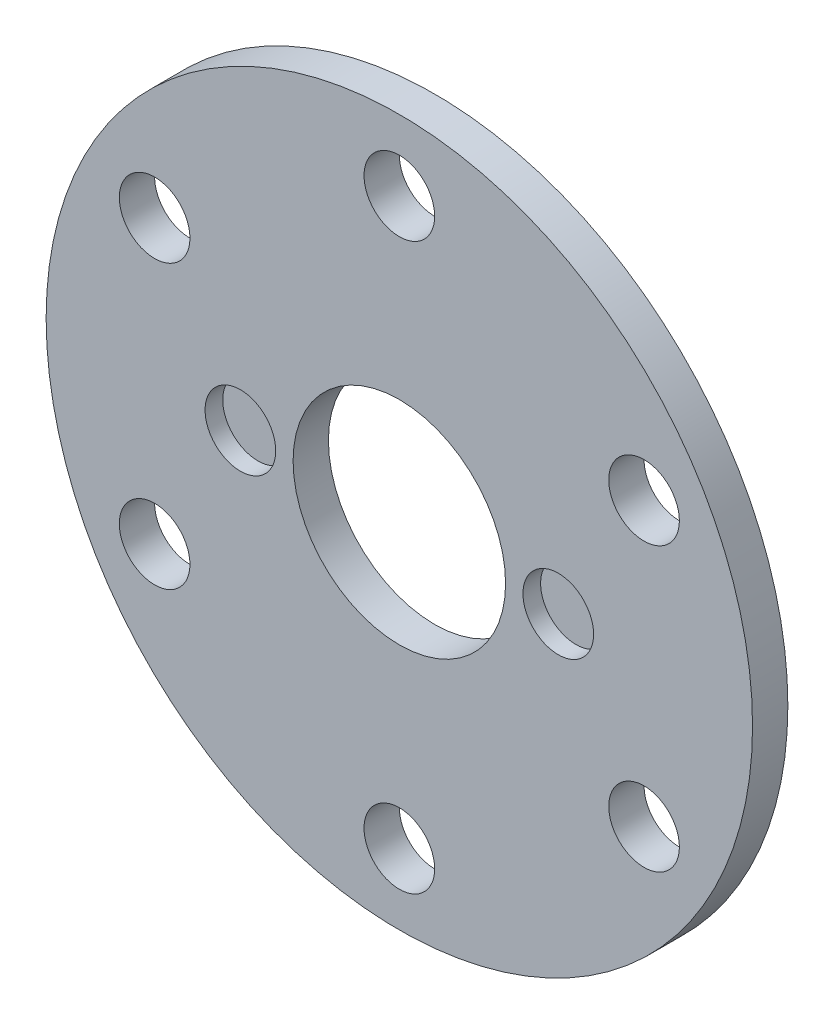
SolidWorks part; units mm, degrees
ref_plane "Front Plane" through (0, 0, 0) normal (0, 0, 1) x (1, 0, 0)
ref_plane "Top Plane" through (0, 0, 0) normal (0, 1, 0) x (1, 0, 0)
ref_plane "Right Plane" through (0, 0, 0) normal (1, 0, 0) x (0, 0, -1)
sketch "Sketch1" plane through (0, 0, 191.2017) normal (0, 0, 1) x (1, 0, 0)
  line L0 (0, 762.7561) -> (0, 788.1561) construction
  line L1 (0, 788.1561) -> (0, 794.5061) construction
  circle A0 centre (0, 762.7561) radius 15.875 construction
  circle A1 centre (0, 762.7561) radius 15.875
  circle A2 centre (0, 762.7561) radius 9.525 construction
  circle A3 centre (0, 762.7561) radius 9.525
  circle A4 centre (-14.2875, 762.7561) radius 3.8735 construction
  circle A5 centre (14.2875, 762.7561) radius 3.8735 construction
  circle A6 centre (-14.2875, 762.7561) radius 3.8735 construction
  circle A7 centre (14.2875, 762.7561) radius 3.8735 construction
  circle A8 centre (0, 762.7561) radius 31.75
  circle A9 centre (0, 788.1561) radius 3.175
  circle A10 centre (21.997, 775.4561) radius 3.175
  circle A11 centre (21.997, 750.0561) radius 3.175
  circle A12 centre (0, 737.3561) radius 3.175
  circle A13 centre (-21.997, 750.0561) radius 3.175
  circle A14 centre (-21.997, 775.4561) radius 3.175
  point P28 (0, 762.7561)
  circle M1 centre (0, 762.7561) radius 15.875
  circle M2 centre (0, 762.7561) radius 9.5504
  dimension "D1" = 63.5
  dimension "D3" = 6.35
  dimension "D2" = 6.35
extrude "Boss-Extrude1" add sketch "Sketch1" along normal blind 3.175 contours A8 A14 A13 A12 A11 A10 A9 M1 | M1 M2
sketch "Sketch2" plane through (0, 0, 194.3767) normal (0, 0, 1) x (1, 0, 0)
  circle A0 centre (-14.2875, 762.7561) radius 3.8735 construction
  circle A1 centre (14.2875, 762.7561) radius 3.8735 construction
  circle A2 centre (-14.2875, 762.7561) radius 3.8735 construction
  circle A3 centre (14.2875, 762.7561) radius 3.8735 construction
  circle A5 centre (-14.2875, 762.7561) radius 3.175
  circle A6 centre (14.2875, 762.7561) radius 3.175
  dimension "D1" = 6.35
extrude "Cut-Extrude1" cut sketch "Sketch2" against normal blind 1.5875
